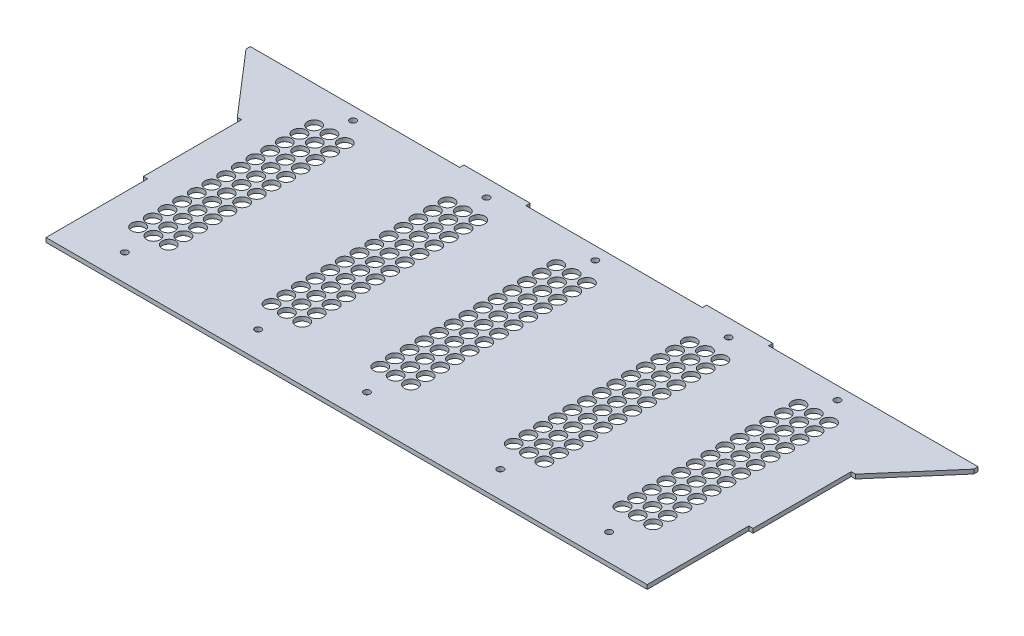
SolidWorks part; units mm, degrees
material "6061-T6 (SS)"
ref_plane "X-Y Datum" through (0, 0, 0) normal (0, 0, 1) x (1, 0, 0)
ref_plane "X-Z Datum" through (0, 0, 0) normal (0, 1, 0) x (1, 0, 0)
ref_plane "Y-Z Datum" through (0, 0, 0) normal (1, 0, 0) x (0, 0, -1)
sketch "Sketch1" plane through (0, 0, 0) normal (0, 0, 1) x (1, 0, 0)
  line L1 (-228.6115, -1.5875) -> (228.6115, -1.5875)
  line L2 (-228.6115, -1.5875) -> (-228.6115, 1.5875)
  line L3 (-228.6115, 1.5875) -> (228.6115, 1.5875)
  line L4 (228.6115, -1.5875) -> (228.6115, 1.5875)
  line L5 (-228.6115, -1.5875) -> (228.6115, 1.5875) construction
  line L6 (-228.6115, 1.5875) -> (228.6115, -1.5875) construction
  point P0 (0, 0)
  dimension "D1" = 3.175
  dimension "D2" = 457.223
extrude "Boss-Extrude1" add sketch "Sketch1" along normal blind 200.642
sketch "Sketch3" plane through (0, 0, 0) normal (0, 0, -1) x (-1, 0, 0)
  line L0 (-66.1907, -1.5583) -> (-66.1907, -1.5875)
  line L9 (228.6115, -1.5875) -> (-228.6115, -1.5875) construction
  line L11 (-228.6115, 1.5875) -> (228.6115, 1.5875) construction
  line L12 (-228.6115, 1.5875) -> (228.6115, 1.5875) construction
  line L13 (-66.1907, -1.5875) -> (-115.8495, -1.5875)
  line L14 (-66.1907, -1.5875) -> (-66.1907, 1.5875)
  line L15 (-66.1907, 1.5875) -> (-115.8495, 1.5875)
  line L16 (-115.8495, -1.5875) -> (-115.8495, 1.5875)
  line L17 (66.1907, -1.5875) -> (115.8495, -1.5875)
  line L18 (66.1907, -1.5875) -> (66.1907, 1.5875)
  line L19 (66.1907, 1.5875) -> (115.8495, 1.5875)
  line L20 (115.8495, -1.5875) -> (115.8495, 1.5875)
  dimension "D2" = 49.6588
sketch "Sketch4" plane through (0, -1.5875, 0) normal (0, -1, 0) x (1, 0, 0)
  line L0 (-228.6115, 0) -> (-272.8865, 0)
  line L2 (-228.6115, 200.642) -> (-228.6115, 0) construction
  line L3 (-228.6115, 50.8) -> (-228.6115, 0)
  line L4 (-272.8865, 0) -> (-272.8865, 3.175)
  line L6 (-228.6115, 50.8) -> (-231.7865, 50.8)
  line L7 (-272.8865, 3.175) -> (-231.7865, 50.8)
  dimension "D1" = 44.275
  dimension "D2" = 50.8
  dimension "D3" = 3.175
  dimension "D4" = 3.175
extrude "Boss-Extrude3" add sketch "Sketch4" against normal blind 3.175
mirror "Mirror1" about plane through (0, 0, 0) normal (1, 0, 0) of "Boss-Extrude3"
sketch "Sketch5" plane through (0, -1.5875, 0) normal (0, -1, 0) x (1, 0, 0)
  line L1 (-228.6115, 200.642) -> (-225.4365, 200.642)
  line L2 (-228.6115, 200.642) -> (-228.6115, 124.442)
  line L3 (-228.6115, 124.442) -> (-225.4365, 124.442)
  line L4 (-225.4365, 200.642) -> (-225.4365, 124.442)
  dimension "D1" = 3.175
  dimension "D2" = 76.2
extrude "Cut-Extrude2" cut sketch "Sketch5" against normal blind 3.175
mirror "Mirror2" about plane through (0, 0, 0) normal (1, 0, 0) of "Cut-Extrude2"
extrude "Boss-Extrude4" add sketch "Sketch3" along normal blind 3.18
sketch "Sketch6" plane through (0, -1.5875, 0) normal (0, -1, 0) x (1, 0, 0)
  point P0 (-186.2355, 9.525)
  point P1 (-186.2355, 180.775)
hole_wizard "M4 Clearance Hole1" positions "Sketch6" profile "Sketch7" hole size "M4" standard "ANSI Metric" end condition through all
sketch "Sketch7" plane through (-186.2355, -1.5875, 9.525) normal (1, 0, 0) x (0, 0, -1)
  line L0 (0, 0) -> (0, 3.175)
  line L1 (0, 3.175) -> (2.4, 3.175)
  line L2 (2.4, 3.175) -> (2.4, 0)
  line L5 (2.4, 0) -> (0, 0)
  line L11 (0, -6.35) -> (0, 107.95) construction
  dimension "Thru Hole Dia." = 4.8
  dimension "Thru Hole Depth" = 3.175
pattern_linear "LPattern5" count 3 spacing 181.614 along (1, 0, 0) of "M4 Clearance Hole1"
sketch "Sketch8" plane through (0, -1.5875, 0) normal (0, -1, 0) x (1, 0, 0)
  point P0 (-86.1905, 9.525)
  point P1 (-86.1905, 180.775)
hole_wizard "M4 Clearance Hole2" positions "Sketch8" profile "Sketch9" hole size "M4" standard "ANSI Metric" end condition through all
sketch "Sketch9" plane through (-86.1905, -1.5875, 9.525) normal (1, 0, 0) x (0, 0, -1)
  line L0 (0, 0) -> (0, 3.175)
  line L1 (0, 3.175) -> (2.4, 3.175)
  line L2 (2.4, 3.175) -> (2.4, 0)
  line L5 (2.4, 0) -> (0, 0)
  line L11 (0, -6.35) -> (0, 107.95) construction
  dimension "Thru Hole Dia." = 4.8
  dimension "Thru Hole Depth" = 3.175
pattern_linear "LPattern6" count 2 spacing 181.614 along (1, 0, 0) of "M4 Clearance Hole2"
sketch "Sketch10" plane through (0, -1.5875, 0) normal (0, -1, 0) x (1, 0, 0)
  circle A0 centre (-174.7355, 159.2567) radius 5 construction
  circle A1 centre (-186.2355, 159.2567) radius 5 construction
  circle A2 centre (-197.7355, 159.2567) radius 5 construction
  circle A3 centre (-174.7355, 159.2567) radius 5
  circle A4 centre (-186.2355, 159.2567) radius 5
  circle A5 centre (-197.7355, 159.2567) radius 5
  circle A6 centre (-74.6905, 159.2567) radius 5 construction
  circle A7 centre (-86.1905, 159.2567) radius 5 construction
  circle A8 centre (-97.6905, 159.2567) radius 5 construction
  circle A9 centre (-74.6905, 159.2567) radius 5
  circle A10 centre (-86.1905, 159.2567) radius 5
  circle A11 centre (-97.6905, 159.2567) radius 5
extrude "Cut-Extrude3" cut sketch "Sketch10" against normal through all contours A5 | A4 | A3
pattern_linear "LPattern1" count 13 spacing 11 along (0, 0, -1) of "Cut-Extrude3"
pattern_linear "LPattern2" count 3 spacing 181.614 along (1, 0, 0) of "Cut-Extrude3", "LPattern1"
sketch "Sketch11" plane through (0, -1.5875, 0) normal (0, -1, 0) x (1, 0, 0)
  circle A1 centre (-74.6905, 159.2567) radius 5
  circle A2 centre (-74.6905, 159.2567) radius 5
  circle A3 centre (-197.7355, 159.2567) radius 5
  circle A4 centre (-197.7355, 159.2567) radius 5
  circle A5 centre (-186.2355, 159.2567) radius 5
  circle A6 centre (-186.2355, 159.2567) radius 5
  circle A7 centre (-174.7355, 159.2567) radius 5
  circle A8 centre (-174.7355, 159.2567) radius 5
  circle A9 centre (-97.6905, 159.2567) radius 5
  circle A10 centre (-97.6905, 159.2567) radius 5
  circle A11 centre (-86.1905, 159.2567) radius 5
  circle A12 centre (-86.1905, 159.2567) radius 5
  dimension "D1" = 0
  dimension "D2" = 0
  dimension "D3" = 0
  dimension "D4" = 0
  dimension "D5" = 0
  dimension "D6" = 0
extrude "Cut-Extrude4" cut sketch "Sketch11" against normal through all contours A10 | A12 | A2
pattern_linear "LPattern3" count 13 spacing 11 along (0, 0, -1) of "Cut-Extrude4"
pattern_linear "LPattern4" count 2 spacing 181.614 along (1, 0, 0) of "LPattern3", "Cut-Extrude4"
